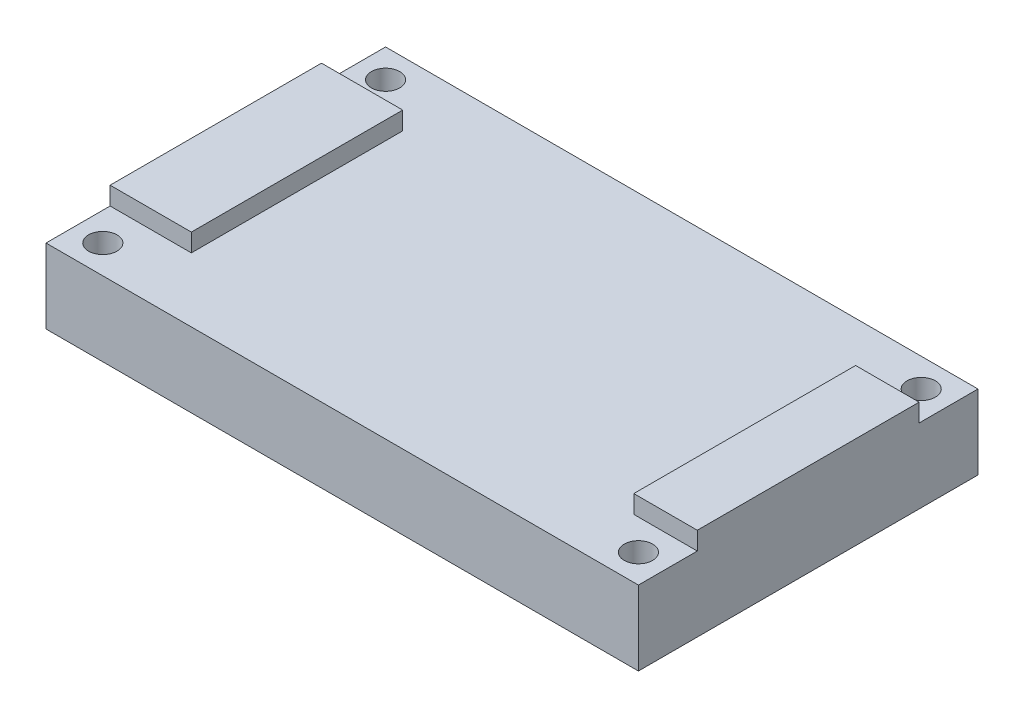
SolidWorks part; units mm, degrees
ref_plane "Front Plane" through (0, 0, 0) normal (0, 0, 1) x (1, 0, 0)
ref_plane "Top Plane" through (0, 0, 0) normal (0, 1, 0) x (1, 0, 0)
ref_plane "Right Plane" through (0, 0, 0) normal (1, 0, 0) x (0, 0, -1)
sketch "Sketch1" plane through (0, 0, 0) normal (0, 1, 0) x (1, 0, 0)
  line L1 (20.8597, -11.957) -> (-20.8597, -11.9571)
  line L2 (20.8597, -11.957) -> (20.8597, 11.9571)
  line L3 (20.8597, 11.9571) -> (-20.8597, 11.957)
  line L4 (-20.8597, -11.9571) -> (-20.8597, 11.957)
  line L5 (20.8597, -11.957) -> (-20.8597, 11.957) construction
  line L6 (20.8597, 11.9571) -> (-20.8597, -11.9571) construction
  point P0 (0, 0)
  dimension "D1" = 23.9141
  dimension "D2" = 41.7195
extrude "Boss-Extrude1" add sketch "Sketch1" along normal blind 5.2451
sketch "Sketch2" plane through (0, 5.2451, 0) normal (0, 1, 0) x (1, 0, 0)
  line L0 (-20.8597, 11.957) -> (-20.8597, -11.9571) construction
  line L1 (20.8597, 11.9571) -> (-20.8597, 11.957) construction
  line L2 (0, 0) -> (-6.3561, 0) construction
  line L3 (0, 0) -> (0, 3.9292) construction
  circle A0 centre (-18.8597, 9.9571) radius 1
  circle A1 centre (18.8597, 9.9571) radius 1
  circle A2 centre (18.8597, -9.9571) radius 1
  circle A3 centre (-18.8597, -9.9571) radius 1
  dimension "D1" = 2
  dimension "D3" = 2
  dimension "D2" = 2
extrude "Cut-Extrude1" cut sketch "Sketch2" against normal through all both and the other way through all
sketch "Sketch3" plane through (0, 5.2451, 0) normal (0, 1, 0) x (1, 0, 0)
  line L0 (0, 0) -> (-7.3731, 0) construction
  line L1 (20.8597, -11.957) -> (20.8597, 11.9571) construction
  line L2 (20.8597, 7.8105) -> (16.3871, 7.8105)
  line L3 (20.8597, 7.8105) -> (20.8598, -7.8105)
  line L4 (20.8598, -7.8105) -> (16.3871, -7.8105)
  line L5 (16.3871, 7.8105) -> (16.3871, -7.8105)
  line L6 (-20.8597, 11.957) -> (-20.8597, -11.9571) construction
  line L7 (-20.8597, 7.4422) -> (-15.139, 7.4422)
  line L8 (-20.8597, 7.4422) -> (-20.8597, -7.4422)
  line L9 (-20.8597, -7.4422) -> (-15.139, -7.4422)
  line L10 (-15.139, 7.4422) -> (-15.139, -7.4422)
  point P9 (16.3871, 0)
  point P16 (-15.139, 0)
  dimension "D1" = 15.621
  dimension "D2" = 14.8844
extrude "Boss-Extrude2" add sketch "Sketch3" along normal blind 1.27
